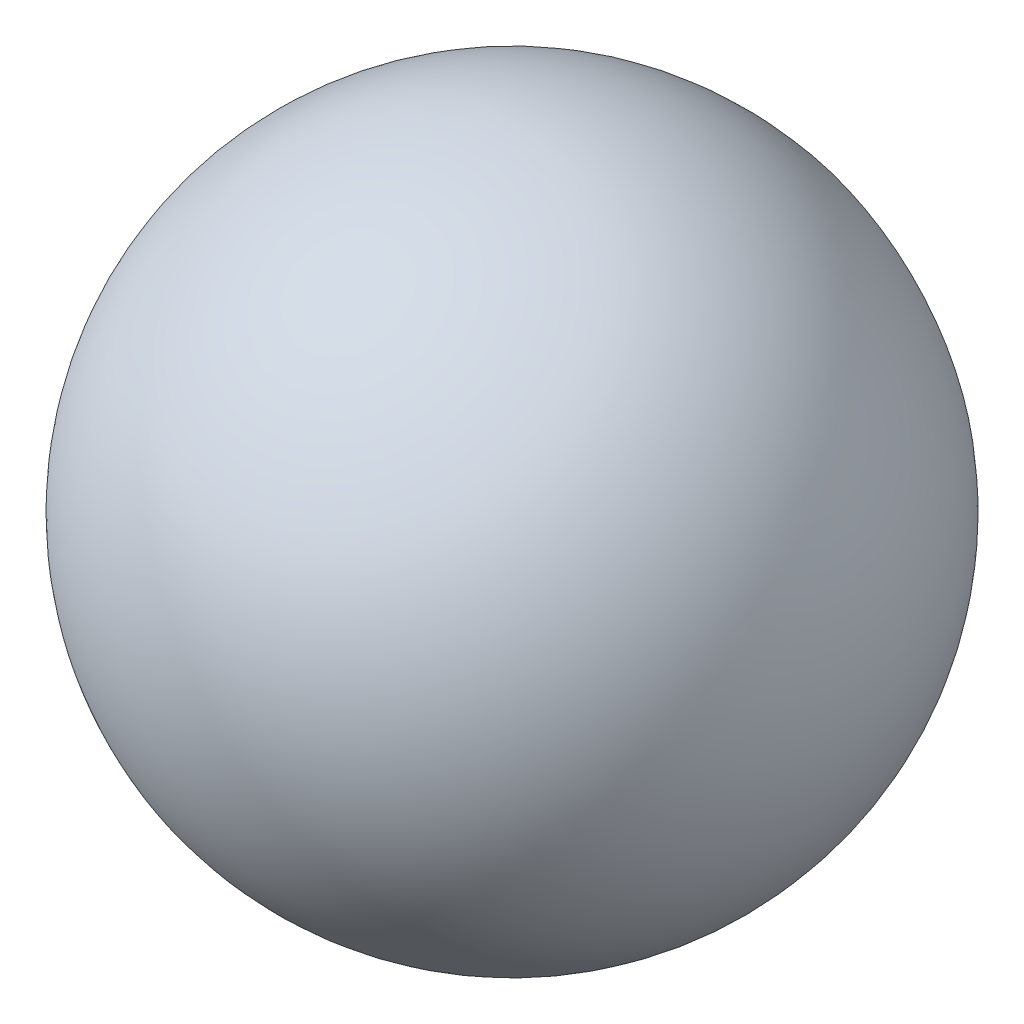
SolidWorks part; units mm, degrees
ref_plane "Front Plane" through (0, 0, 0) normal (0, 0, 1) x (1, 0, 0)
ref_plane "Top Plane" through (0, 0, 0) normal (0, 1, 0) x (1, 0, 0)
ref_plane "Right Plane" through (0, 0, 0) normal (1, 0, 0) x (0, 0, -1)
sketch "Sketch1" plane through (0, 0, 0) normal (0, 1, 0) x (1, 0, 0)
  line L0 (0, 58.4175) -> (0, -51.513) construction
  line L1 (0, 21.1148) -> (17.6186, 21.1148)
  line L2 (0, 21.1148) -> (0, -27.5)
  arc A0 (0, -27.5) -> (17.6186, 21.1148) centre (0, 0) ccw
  dimension "D1" = 55
revolve "Revolve1" add sketch "Sketch1" angle 360 about L0
